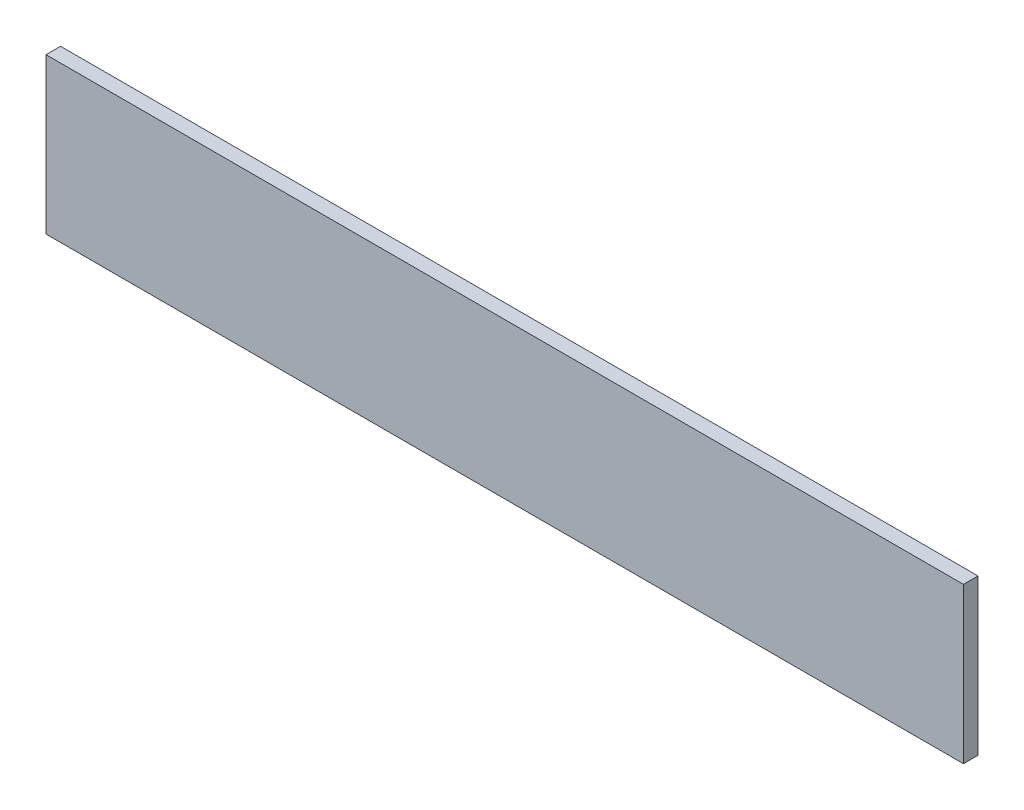
SolidWorks part; units mm, degrees
ref_plane "前视基准面" through (0, 0, 0) normal (0, 0, 1) x (1, 0, 0)
ref_plane "上视基准面" through (0, 0, 0) normal (0, 1, 0) x (1, 0, 0)
ref_plane "右视基准面" through (0, 0, 0) normal (1, 0, 0) x (0, 0, -1)
sketch "草图1" plane through (0, 0, 0) normal (0, 0, 1) x (1, 0, 0)
  line L1 (-94.5, 16) -> (94.5, 16)
  line L2 (-94.5, 16) -> (-94.5, -16)
  line L3 (-94.5, -16) -> (94.5, -16)
  line L4 (94.5, 16) -> (94.5, -16)
  line L5 (-94.5, 16) -> (94.5, -16) construction
  line L6 (-94.5, -16) -> (94.5, 16) construction
  point P0 (0, 0)
  dimension "D1" = 189
  dimension "D2" = 32
extrude "凸台-拉伸1" add sketch "草图1" along normal mid plane 3
